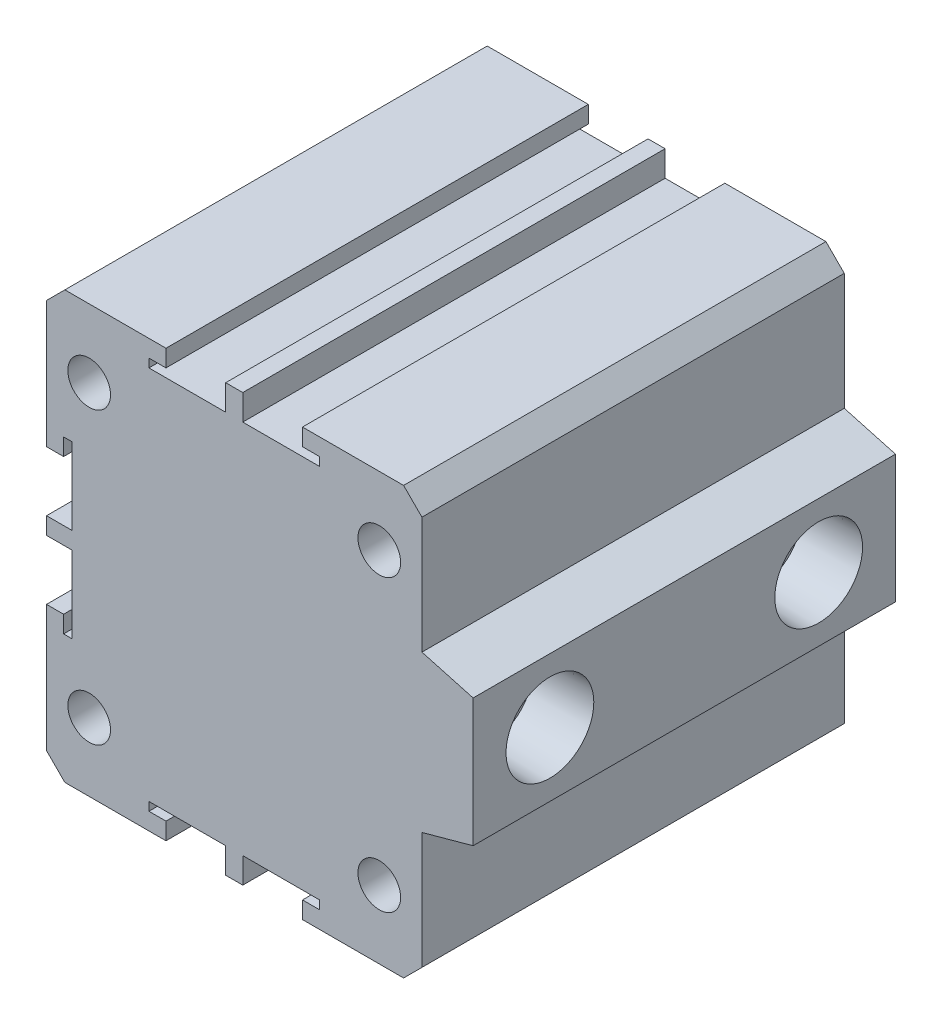
SolidWorks part; units mm, degrees
material "6061-O (SS)"
ref_plane "Alzado" through (0, 0, 0) normal (0, 0, 1) x (1, 0, 0)
ref_plane "Planta" through (0, 0, 0) normal (0, 1, 0) x (1, 0, 0)
ref_plane "Vista lateral" through (0, 0, 0) normal (1, 0, 0) x (0, 0, -1)
sketch "Croquis1" plane through (0, 0, 0) normal (0, 0, 1) x (1, 0, 0)
  line L0 (-22, 22.85) -> (-19.85, 25)
  line L1 (-19.85, 25) -> (-8, 25)
  line L2 (-22, 22.85) -> (-22, 8)
  line L3 (-19.85, -25) -> (-8, -25)
  line L4 (22, 22.85) -> (22, 9.15)
  line L5 (-22, 25) -> (22, -25) construction
  line L6 (-22, -25) -> (22, 25) construction
  line L7 (19.85, 25) -> (22, 22.85)
  line L8 (19.85, -25) -> (22, -22.85)
  line L9 (-22, -22.85) -> (-19.85, -25)
  line L10 (22, 9.15) -> (28, 7.5)
  line L11 (28, 7.5) -> (28, -7.5)
  line L12 (28, -7.5) -> (22, -9.15)
  line L13 (22, -9.15) -> (22, -22.85)
  line L14 (-8, 25) -> (-8, 23)
  line L15 (-8, 23) -> (-10, 23)
  line L16 (-10, 23) -> (-10, 22)
  line L17 (-10, 22) -> (-1, 22)
  line L18 (10, 22) -> (10, 23)
  line L19 (10, 23) -> (8, 23)
  line L20 (8, 23) -> (8, 25)
  line L21 (8, 25) -> (19.85, 25)
  line L22 (0, 0) -> (0, 50000) construction
  line L23 (-1, 22) -> (-1, 25)
  line L24 (-1, 25) -> (1, 25)
  line L25 (1, 25) -> (1, 22)
  line L26 (1, 22) -> (10, 22)
  line L27 (-22, -8) -> (-20, -8)
  line L28 (-20, -8) -> (-20, -10)
  line L29 (-19, -10) -> (-19, -1)
  line L30 (-20, -10) -> (-19, -10)
  line L31 (-19, -1) -> (-22, -1)
  line L32 (-22, -1) -> (-22, 1)
  line L33 (-22, 1) -> (-19, 1)
  line L34 (-19, 1) -> (-19, 10)
  line L35 (-19, 10) -> (-20, 10)
  line L36 (-20, 10) -> (-20, 8)
  line L37 (-20, 8) -> (-22, 8)
  line L38 (-22, -8) -> (-22, -22.85)
  line L39 (-22, 1) -> (-22, -1)
  line L40 (0, 0) -> (50000, 0) construction
  line L41 (1, -22) -> (10, -22)
  line L42 (1, -25) -> (1, -22)
  line L43 (-1, -25) -> (1, -25)
  line L44 (-1, -22) -> (-1, -25)
  line L45 (8, -23) -> (8, -25)
  line L46 (10, -23) -> (8, -23)
  line L47 (10, -22) -> (10, -23)
  line L48 (-10, -22) -> (-1, -22)
  line L49 (11, -22) -> (11, -20) [skipped]
  line L50 (11, -20) -> (13, -20) [skipped]
  line L51 (13, -19) -> (4, -19) [skipped]
  line L52 (13, -20) -> (13, -19) [skipped]
  line L53 (4, -19) -> (4, -22) [skipped]
  line L54 (4, -22) -> (2, -22) [skipped]
  line L55 (2, -22) -> (2, -19) [skipped]
  line L56 (2, -19) -> (-7, -19) [skipped]
  line L57 (-7, -19) -> (-7, -20) [skipped]
  line L58 (-7, -20) -> (-5, -20) [skipped]
  line L59 (-5, -20) -> (-5, -22) [skipped]
  line L60 (-10, -23) -> (-10, -22)
  line L61 (-8, -23) -> (-10, -23)
  line L62 (-8, -25) -> (-8, -23)
  line L63 (8, -25) -> (19.85, -25)
  line L64 (-1, -25) -> (1, -25)
  point P0 (0, 0)
  point P17 (28, 0)
  point P25 (0, 25)
  point P49 (-22, 0)
  dimension "D1" = 50
  dimension "D2" = 44
  dimension "D3" = 15
  dimension "D4" = 18.3
  dimension "D9" = 50
  dimension "D10" = 2
  dimension "D11" = 1
  dimension "D12" = 20
  dimension "D13" = 3
extrude "Saliente-Extruir1" add sketch "Croquis1" along normal mid plane 49.5 contours L45 L63 L8 L13 L12 L11 L10 L4 L7 L21 L20 L19 L18 L26 L25 L24 L23 L17 L16 L15 L14 L1 L0 L2 L37 L36 L35 L34 L33 L32 L31 L29 L30 L28 L27 L38 L9 L3 L62 L61 L60 L48 L44 L43 L42 L41 L47 L46
sketch "Croquis2" plane through (0, 0, 0) normal (0, 1, 0) x (1, 0, 0)
  line L0 (0, 24.75) -> (0, 27.75)
  line L8 (0, 27.75) -> (11, 27.75)
  line L9 (11, 27.75) -> (11, 24.75)
  line L10 (11, 24.75) -> (0, 24.75)
  line L11 (1, 24.75) -> (10, 24.75) construction
  dimension "D1" = 11
  dimension "D3" = 3
revolve "Revolución1" add sketch "Croquis2" angle 360 about L0
sketch "Croquis3" plane through (0, 0, -27.75) normal (0, 0, -1) x (-1, 0, 0)
  circle A0 centre (0, 0) radius 6
  dimension "D1" = 12
extrude "Cortar-Extruir1" cut sketch "Croquis3" against normal blind 46
sketch "Croquis4" plane through (0, 0, -24.75) normal (0, 0, -1) x (-1, 0, 0)
  circle A0 centre (0, 0) radius 11 construction
  circle A1 centre (0, 0) radius 11
  circle A2 centre (0, 0) radius 16
  dimension "D1" = 5
extrude "Cortar-Extruir2" cut sketch "Croquis4" against normal blind 5
hole_wizard "Taladro roscado M61" positions "Croquis5" profile "Croquis6" tap size "M6" standard "DIN" end condition through all
sketch "Croquis5" plane through (0, 0, -24.75) normal (0, 0, -1) x (-1, 0, 0)
  line L0 (0, 0) -> (17, -17) construction
  point P0 (17, -17)
  point P7 (-17, -17)
  point P8 (-17, 17)
  point P9 (17, 17)
  dimension "D2" = 24.0416
  dimension "D3" = 34
  dimension "D1" = 4
sketch "Croquis6" plane through (-17, -17, -24.75) normal (1, 0, 0) x (0, 1, 0)
  line L0 (0, 0) -> (0, 49.5)
  line L1 (0, 49.5) -> (2.5, 49.5)
  line L2 (2.5, 49.5) -> (2.5, 0)
  line L5 (2.5, 0) -> (0, 0)
  line L11 (0, -6.35) -> (0, 107.95) construction
  dimension "Diámetro de perforador para roscar hasta el siguiente" = 5
  dimension "Profundidad de perforador para roscar hasta el siguiente" = 49.5
cosmetic thread "Rosca de taladro2"
cosmetic thread "Rosca de taladro3"
cosmetic thread "Rosca de taladro4"
cosmetic thread "Rosca de taladro5"
hole_wizard "Taladro roscado 1/8 NPT1" positions "Croquis10" profile "Croquis11" size "1/8" standard "Ansi Inch"
sketch "Croquis10" plane through (28, 0, 0) normal (1, 0, 0) x (0, 0, -1)
  line L0 (0, 50000) -> (0, -50000) construction
  point P0 (15.75, 0)
  point P2 (-15.75, 0)
  point P14 (0, 0)
  dimension "D1" = 9
sketch "Croquis11" plane through (28, 0, -15.75) normal (0, 1, 0) x (0, 0, -1)
  line L0 (0, 0) -> (0, 14.1535)
  line L1 (4.2164, 11.62) -> (0, 14.1535)
  line L2 (-4.2164, 11.62) -> (0, 14.1535) construction
  line L3 (4.2164, 11.62) -> (4.2164, 6.92)
  line L4 (4.2164, 6.92) -> (4.9362, 6.92)
  line L5 (4.9362, 6.92) -> (5.1434, 0)
  line L6 (-4.9362, 6.92) -> (-5.1434, 0) construction
  line L7 (5.1434, 0) -> (0, 0)
  line L8 (0, -6.35) -> (0, 107.95) construction
  line L11 (-4.2164, 6.92) -> (-4.9362, 6.92) construction
  dimension "Diámetro de perforador para roscar" = 8.4328
  dimension "Profundidad de perforador para roscar" = 11.62
  dimension "Diámetro de rosca" = 10.2867
  dimension "Ángulo de rosca" = 3.43
  dimension "Profundidad de rosca" = 6.92
  dimension "Ángulo de perforador" = 118
